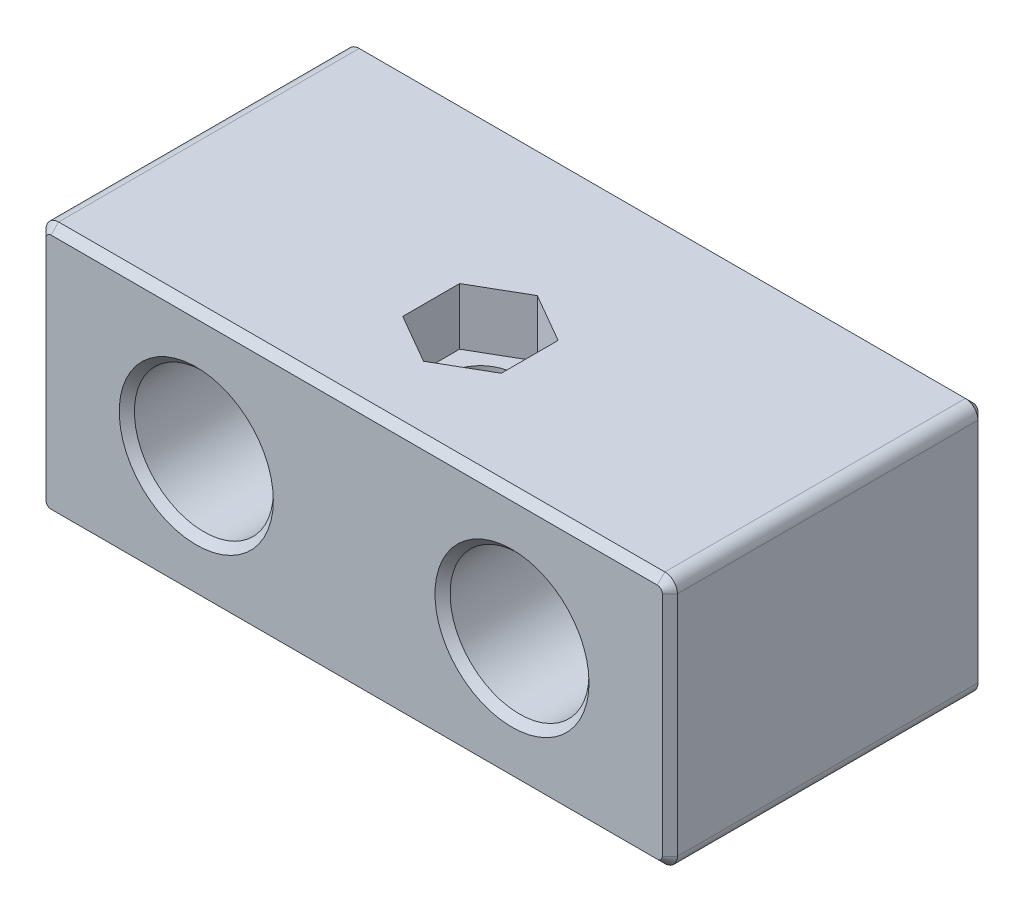
SolidWorks part; units mm, degrees
material "ABS"
ref_plane "Front Plane" through (0, 0, 0) normal (0, 0, 1) x (1, 0, 0)
ref_plane "Top Plane" through (0, 0, 0) normal (0, 1, 0) x (1, 0, 0)
ref_plane "Right Plane" through (0, 0, 0) normal (1, 0, 0) x (0, 0, -1)
sketch "Sketch1" plane through (0, 0, 0) normal (0, 0, 1) x (1, 0, 0)
  line L1 (25, -10) -> (-25, -10)
  line L2 (25, -10) -> (25, 10)
  line L3 (25, 10) -> (-25, 10)
  line L4 (-25, -10) -> (-25, 10)
  line L5 (25, -10) -> (-25, 10) construction
  line L6 (25, 10) -> (-25, -10) construction
  point P0 (0, 0)
  dimension "D1" = 50
  dimension "D2" = 20
extrude "Boss-Extrude1" add sketch "Sketch1" along normal blind 25
hole_wizard "CBORE for M6 Hex Socket Head Cap Screw1" positions "Sketch2" profile "Sketch4" counterbore size "M6" standard "DIN" end condition through all
sketch "Sketch2" plane through (0, 0, 25) normal (0, 0, 1) x (1, 0, 0)
  line L0 (0, 10) -> (0, -10) construction
  line L1 (25, 10) -> (-25, 10) construction
  line L2 (-25, -10) -> (25, -10) construction
  point P0 (-12.5, 0)
  point P2 (12.5, 0)
  point P11 (0, 0)
  dimension "D1" = 25
sketch "Sketch4" plane through (-12.5, 0, 25) normal (1, 0, 0) x (0, -1, 0)
  line L0 (0, 0) -> (0, 25)
  line L1 (0, 25) -> (3.2, 25)
  line L3 (3.2, 25) -> (3.2, 12)
  line L4 (3.2, 12) -> (5.5, 12)
  line L5 (5.5, 12) -> (5.5, 0)
  line L7 (5.5, 0) -> (0, 0)
  line L11 (0, -6.35) -> (0, 107.95) construction
  dimension "Thru Hole Dia." = 6.4
  dimension "Thru Hole Depth" = 25
  dimension "C'Bore Dia." = 11
  dimension "C'Bore Depth" = 12
hole_wizard "M5 Clearance Hole1" positions "Sketch5" profile "Sketch6" hole size "M5" standard "DIN" end condition through all
sketch "Sketch5" plane through (0, -10, 0) normal (0, -1, 0) x (-1, 0, 0)
  line L1 (25, 0) -> (-25, 0) construction
  point P0 (0, -15)
  point P5 (0, 0)
  point P8 (0, 0)
  dimension "D1" = 15
sketch "Sketch6" plane through (0, -10, 15) normal (1, 0, 0) x (0, 0, -1)
  line L0 (0, 0) -> (0, 20)
  line L1 (0, 20) -> (2.75, 20)
  line L2 (2.75, 20) -> (2.75, 0)
  line L5 (2.75, 0) -> (0, 0)
  line L11 (0, -6.35) -> (0, 107.95) construction
  dimension "Thru Hole Dia." = 5.5
  dimension "Thru Hole Depth" = 20
sketch "Sketch7" plane through (0, 10, 0) normal (0, 1, 0) x (1, 0, 0)
  line L0 (0, -15) -> (0, -19.5033) construction
  line L1 (3.9, -12.7483) -> (0, -10.4967)
  line L2 (0, -10.4967) -> (-3.9, -12.7483)
  line L3 (-3.9, -12.7483) -> (-3.9, -17.2517)
  line L4 (-3.9, -17.2517) -> (0, -19.5033)
  line L5 (0, -19.5033) -> (3.9, -17.2517)
  line L6 (3.9, -17.2517) -> (3.9, -12.7483)
  circle A0 centre (0, -15) radius 3.9 construction
  dimension "D1" = 7.8
extrude "Cut-Extrude1" cut sketch "Sketch7" against normal blind 4.5
fillet "Fillet1" radius 1 4 edges at (-25, 10, 12.5) (-25, -10, 12.5) (25, 10, 12.5) (25, -10, 12.5)
chamfer "Chamfer1" distance 0.6 angle 45 20 edges at (24.7071, 9.7071, 25) (25, 0, 25) (24.7071, -9.7071, 25) (0, -10, 25) (-24.7071, -9.7071, 25) (-25, 0, 25) (-24.7071, 9.7071, 25) (0, 10, 25) (18, 0, 25) (-7, 0, 25) (-24.7071, -9.7071, 0) (0, -10, 0) (24.7071, -9.7071, 0) (25, 0, 0) (24.7071, 9.7071, 0) (0, 10, 0) (-24.7071, 9.7071, 0) (-25, 0, 0) (15.7, 0, 0) (-9.3, 0, 0)
